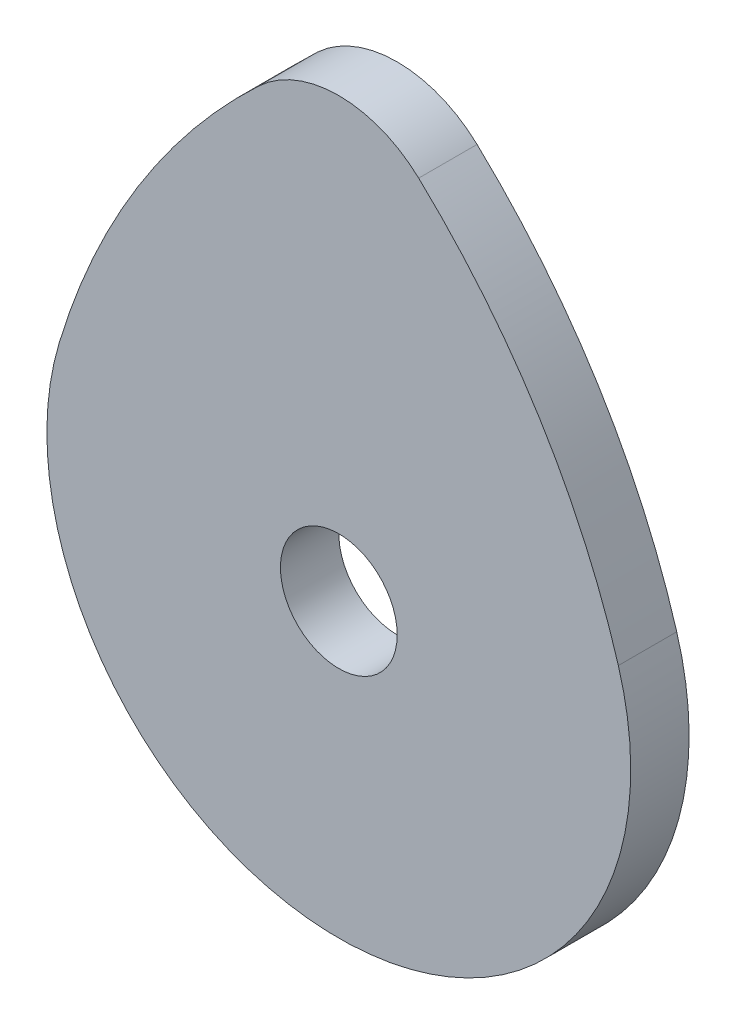
SolidWorks part; units mm, degrees
ref_plane "Front Plane" through (0, 0, 0) normal (0, 0, 1) x (1, 0, 0)
ref_plane "Top Plane" through (0, 0, 0) normal (0, 1, 0) x (1, 0, 0)
ref_plane "Right Plane" through (0, 0, 0) normal (1, 0, 0) x (0, 0, -1)
sketch "Sketch1" plane through (0, 0, 0) normal (0, 0, 1) x (1, 0, 0)
  line L0 (0, 501.5149) -> (0, 381) construction
  arc A1 (-243.2474, 73.1212) -> (243.2474, 73.1212) centre (0, 0) ccw
  arc A4 (-69.4993, 353.5108) -> (-243.2474, 73.1212) centre (364.8711, -109.6818) ccw
  arc A5 (69.4993, 353.5108) -> (243.2474, 73.1212) centre (-364.8711, -109.6818) cw
  arc A6 (69.4993, 353.5108) -> (-69.4993, 353.5108) centre (0, 279.4) ccw
  circle A7 centre (0, 0) radius 50.8
  dimension "D1" = 101.6
  dimension "D3" = 508
  dimension "D6" = 1270
  dimension "D5" = 279.4
extrude "Boss-Extrude1" add sketch "Sketch1" along normal blind 50.8
